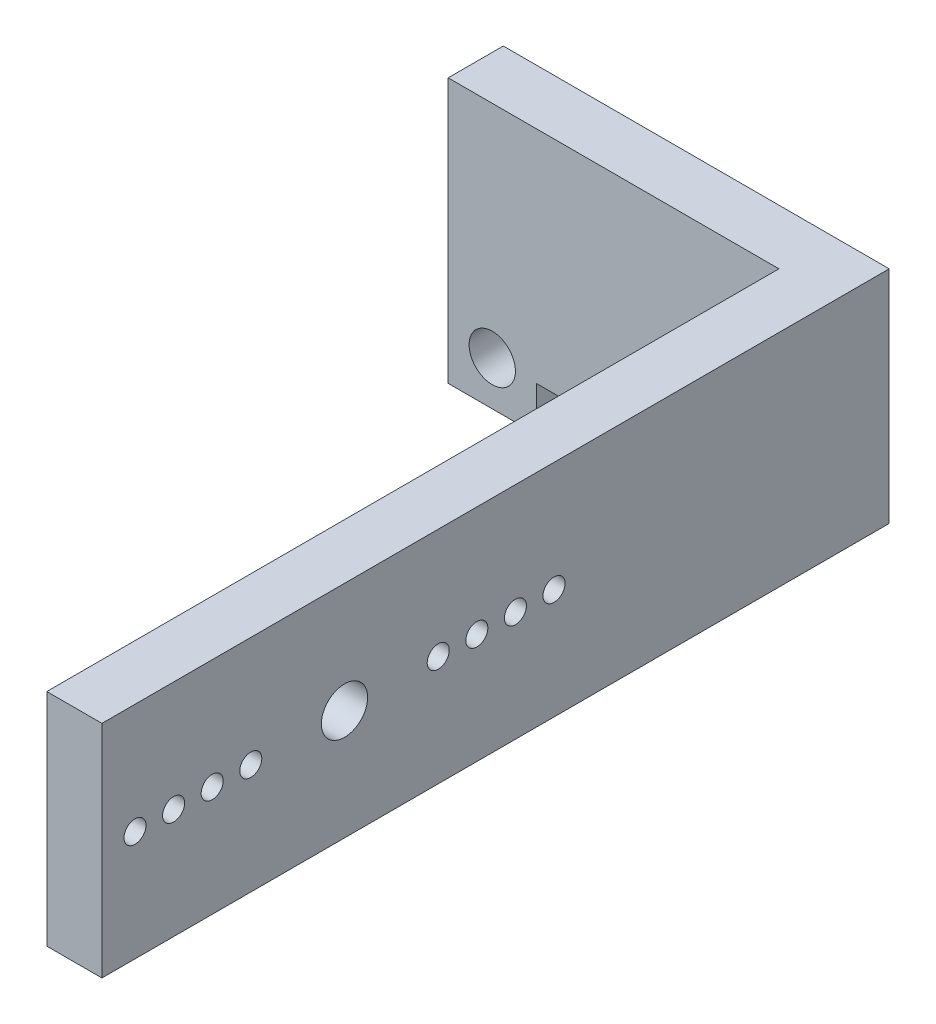
SolidWorks part; units mm, degrees
ref_plane "Alzado" through (0, 0, 0) normal (0, 0, 1) x (1, 0, 0)
ref_plane "Planta" through (0, 0, 0) normal (0, 1, 0) x (1, 0, 0)
ref_plane "Vista lateral" through (0, 0, 0) normal (1, 0, 0) x (0, 0, -1)
sketch "Croquis1" plane through (0, 0, 0) normal (0, 0, 1) x (1, 0, 0)
  line L1 (-4, 20) -> (26, 20)
  line L2 (-4, 20) -> (-4, 0)
  line L3 (-4, 0) -> (26, 0)
  line L4 (26, 20) -> (26, 0)
  line L10 (-4, 0) -> (4, 0)
  line L11 (-4, 0) -> (-4, -4)
  line L12 (-4, -4) -> (4, -4)
  line L13 (4, 0) -> (4, -4)
  circle A0 centre (0, 0) radius 2.1
  dimension "D1" = 4.2
  dimension "D2" = 20
  dimension "D3" = 4
  dimension "D4" = 26
  dimension "D6" = 8
  dimension "D7" = 4
extrude "Saliente-Extruir1" add sketch "Croquis1" along normal blind 5 contours A0 L3 L4 L1 L2 | A0 L3 L11 L12 L13
sketch "Croquis2" plane through (26, 0, 0) normal (1, 0, 0) x (0, 0, -1)
  line L1 (0, 0) -> (-71.4, 0)
  line L2 (0, 0) -> (0, 20)
  line L3 (0, 20) -> (-71.4, 20)
  line L4 (-71.4, 0) -> (-71.4, 20)
  line L5 (-49.4, 10) -> (-9.4, 10) construction
  line L6 (0, 0) -> (-9.4, 0)
  line L7 (0, 0) -> (0, 20)
  line L8 (0, 20) -> (-9.4, 20)
  line L9 (-9.4, 0) -> (-9.4, 20) construction
  circle A0 centre (-49.4, 10) radius 2.1
  dimension "D2" = 22
  dimension "D4" = 4.2
  dimension "D1" = 40
  dimension "D3" = 9.4
extrude "Saliente-Extruir2" add sketch "Croquis2" along normal blind 5
sketch "Croquis3" plane through (31, 0, 0) normal (1, 0, 0) x (0, 0, -1)
  line L0 (0, 20) -> (-71.4, 20) construction
  line L1 (-41.4, 20) -> (-35.4, 20)
  line L2 (-41.4, 20) -> (-41.4, 0)
  line L3 (-41.4, 0) -> (-35.4, 0)
  line L4 (-35.4, 20) -> (-35.4, 0)
  line L5 (0, 0) -> (-71.4, 0) construction
  line L6 (-49.4, 10) -> (-57.4, 10) construction
  line L7 (-57.4, 20) -> (-63.4, 20)
  line L8 (-57.4, 20) -> (-57.4, 0)
  line L9 (-57.4, 0) -> (-63.4, 0)
  line L10 (-63.4, 20) -> (-63.4, 0)
  line L11 (-49.4, 10) -> (-41.4, 10) construction
  dimension "D1" = 6
  dimension "D2" = 8
extrude "Saliente-Extruir3" [suppressed] add sketch "Croquis3" along normal blind 10
sketch "Croquis4" plane through (31, 0, 0) normal (1, 0, 0) x (0, 0, -1)
  line L0 (-71.4, 10) -> (0, 10) construction
  line L1 (-57.9, 10) -> (-40.9, 10)
  line L2 (-40.9, 11) -> (-49.4, 11) construction
  line L3 (-68.4, 11) -> (-64.9, 11) construction
  line L4 (-64.9, 11) -> (-61.4, 11) construction
  line L5 (-61.4, 11) -> (-57.9, 11) construction
  line L6 (-57.9, 10) -> (-49.4, 10) construction
  line L7 (-40.9, 11) -> (-37.4, 11) construction
  line L8 (-37.4, 11) -> (-33.9, 11) construction
  line L9 (-33.9, 11) -> (-30.4, 11) construction
  line L10 (-49.4, 11) -> (-57.9, 11) construction
  line L11 (-71.4, 0) -> (-71.4, 20) construction
  line L12 (0, 0) -> (0, 20) construction
  line L13 (-49.4, 11) -> (-49.4, 10) construction
  circle A0 centre (-68.4, 10) radius 1
  circle A1 centre (-64.9, 10) radius 1
  circle A2 centre (-61.4, 10) radius 1
  circle A3 centre (-57.9, 10) radius 1
  circle A4 centre (-40.9, 10) radius 1
  circle A5 centre (-37.4, 10) radius 1
  circle A6 centre (-33.9, 10) radius 1
  circle A7 centre (-30.4, 10) radius 1
  circle A8 centre (-49.4, 10) radius 2.1 construction
  dimension "D1" = 2
  dimension "D3" = 3.5
  dimension "D4" = 8.5
extrude "Cortar-Extruir1" cut sketch "Croquis4" against normal up to next contours A7 | A6 | A5 | A4 | A1 | A0 | A2 | A3
sketch "Croquis5" plane through (31, 0, 0) normal (1, 0, 0) x (0, 0, -1)
  circle A0 centre (-57.9, 10) radius 2.1
  circle A1 centre (-64.9, 10) radius 2.1
  circle A2 centre (-40.9, 10) radius 2.1
  circle A3 centre (-33.9, 10) radius 2.1
  dimension "D1" = 4.2
extrude "Cortar-Extruir2" cut sketch "Croquis5" along normal blind 3 from surface at -5 starting at face at (26, 10, 29.4)
